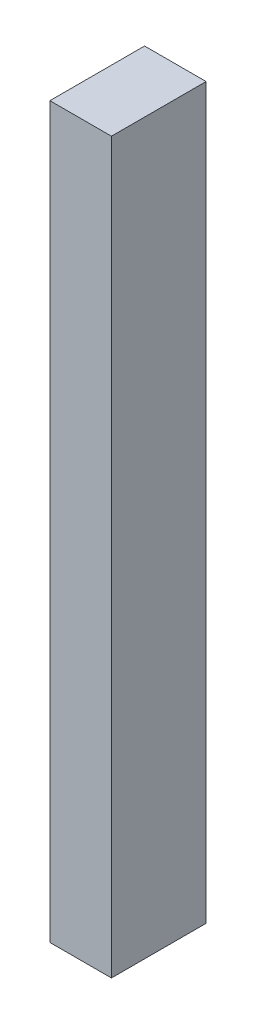
SolidWorks part; units mm, degrees
ref_plane "Alzado" through (0, 0, 0) normal (0, 0, 1) x (1, 0, 0)
ref_plane "Planta" through (0, 0, 0) normal (0, 1, 0) x (1, 0, 0)
ref_plane "Vista lateral" through (0, 0, 0) normal (1, 0, 0) x (0, 0, -1)
sketch "Croquis1" plane through (0, 0, 0) normal (0, 1, 0) x (1, 0, 0)
  line L0 (5.5287, 0) -> (-5.5287, 0) construction
  line L2 (3.25, 5) -> (-3.25, 5)
  line L3 (3.25, 5) -> (3.25, -5)
  line L4 (3.25, -5) -> (-3.25, -5)
  line L5 (-3.25, 5) -> (-3.25, -5)
  line L6 (3.25, 5) -> (-3.25, -5) construction
  line L7 (3.25, -5) -> (-3.25, 5) construction
  point P0 (0, 0)
  point P4 (0, 0)
  dimension "D1" = 6.5
  dimension "D2" = 10
extrude "Saliente-Extruir1" add sketch "Croquis1" along normal blind 77
